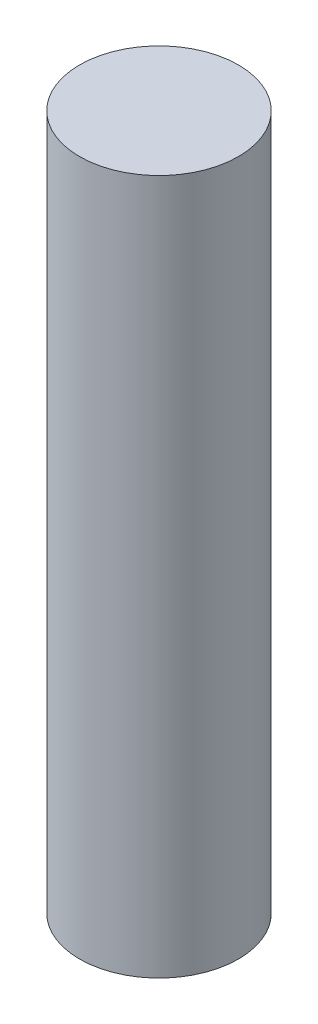
SolidWorks part; units mm, degrees
ref_plane "Front Plane" through (0, 0, 0) normal (0, 0, 1) x (1, 0, 0)
ref_plane "Top Plane" through (0, 0, 0) normal (0, 1, 0) x (1, 0, 0)
ref_plane "Right Plane" through (0, 0, 0) normal (1, 0, 0) x (0, 0, -1)
sketch "Sketch1" plane through (0, 0, 0) normal (0, 1, 0) x (1, 0, 0)
  circle A0 centre (0, 0) radius 101.6
  dimension "D1" = 203.2
extrude "Boss-Extrude1" add sketch "Sketch1" along normal blind 889
